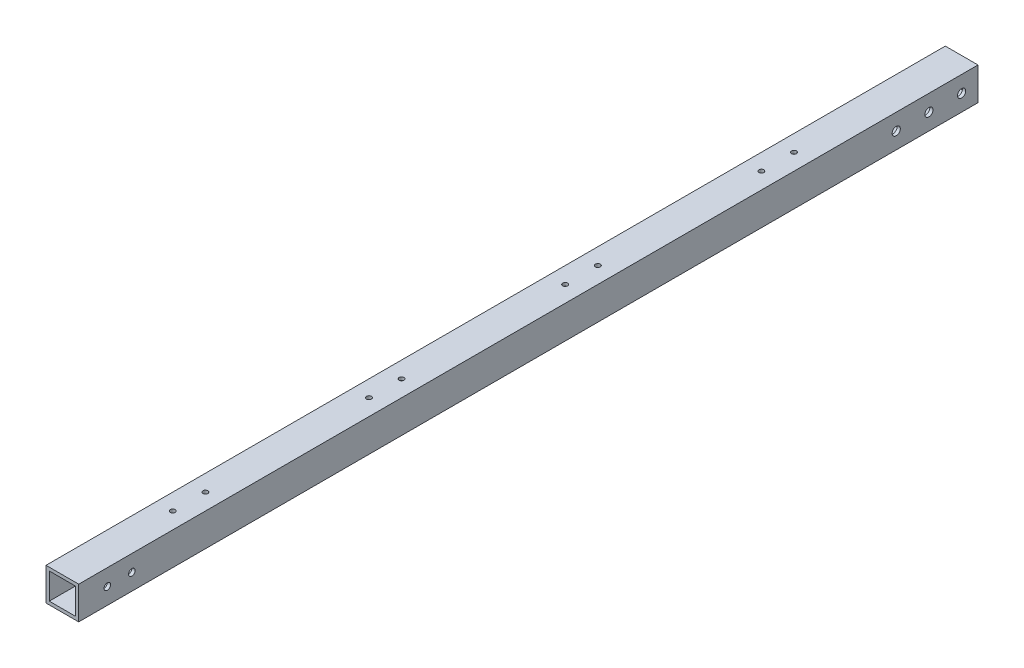
SolidWorks part; units mm, degrees
material "3.0205 (EN-AW 1200)"
ref_plane "前视基准面" through (0, 0, 0) normal (0, 0, 1) x (1, 0, 0)
ref_plane "上视基准面" through (0, 0, 0) normal (0, 1, 0) x (1, 0, 0)
ref_plane "右视基准面" through (0, 0, 0) normal (1, 0, 0) x (0, 0, -1)
sketch "草图1" plane through (0, 0, 0) normal (0, 0, 1) x (1, 0, 0)
  line L1 (-10, -10) -> (10, -10)
  line L2 (-10, -10) -> (-10, 10)
  line L3 (-10, 10) -> (10, 10)
  line L4 (10, -10) -> (10, 10)
  line L5 (-10, -10) -> (10, 10) construction
  line L6 (-10, 10) -> (10, -10) construction
  line L7 (-8, -8) -> (8, -8)
  line L8 (-8, -8) -> (-8, 8)
  line L9 (-8, 8) -> (8, 8)
  line L10 (8, -8) -> (8, 8)
  line L11 (-8, -8) -> (8, 8) construction
  line L12 (-8, 8) -> (8, -8) construction
  point P0 (0, 0)
  point P6 (0, 0)
  dimension "D1" = 16
  dimension "D2" = 20
  dimension "D3" = 20
extrude "凸台-拉伸1" add sketch "草图1" along normal blind 550
sketch "Sketch1" plane through (-10, 0, 0) normal (-1, 0, 0) x (0, 0, 1)
  line L0 (550, 0) -> (541.2704, 0) construction
  line L1 (550, 10) -> (550, -10) construction
  circle A0 centre (532.5, 0) radius 2
  circle A1 centre (517.5, 0) radius 2
  dimension "D1" = 4
  dimension "D2" = 4
  dimension "D4" = 17.5
  dimension "D3" = 15
extrude "Cut-Extrude1" cut sketch "Sketch1" against normal blind 20
sketch "Sketch2" plane through (-10, 0, 0) normal (-1, 0, 0) x (0, 0, 1)
  line L0 (0, 0) -> (73.8513, 0) construction
  line L1 (0, 10) -> (0, -10) construction
  circle A0 centre (10, 0) radius 2.5
  circle A1 centre (30, 0) radius 2.5
  circle A3 centre (50, 0) radius 2.5
  dimension "D3" = 5
  dimension "D4" = 5
  dimension "D5" = 5
  dimension "D1" = 10
  dimension "D2" = 20
  dimension "D6" = 20
extrude "Cut-Extrude2" cut sketch "Sketch2" against normal blind 20
sketch "Sketch5" plane through (0, -10, 0) normal (0, -1, 0) x (1, 0, 0)
  line L0 (0, 0) -> (0, 550) construction
  line L1 (-10, 550) -> (10, 550) construction
  circle A0 centre (0, 482.5) radius 1.5
  circle A1 centre (0, 462.5) radius 1.5
  circle A2 centre (0, 362.5) radius 1.5
  circle A3 centre (0, 342.5) radius 1.5
  circle A4 centre (0, 242.5) radius 1.5
  circle A5 centre (0, 222.5) radius 1.5
  circle A6 centre (0, 122.5) radius 1.5
  circle A7 centre (0, 102.5) radius 1.5
  dimension "D1" = 67.5
  dimension "D3" = 3
  dimension "D4" = 3
  dimension "D5" = 3
  dimension "D6" = 3
  dimension "D7" = 20
  dimension "D8" = 100
  dimension "D9" = 3
  dimension "D10" = 3
  dimension "D12" = 100
  dimension "D13" = 3
  dimension "D14" = 3
  dimension "D15" = 20
  dimension "D16" = 100
  dimension "D2" = 20
  dimension "D11" = 20
extrude "Cut-Extrude3" cut sketch "Sketch5" against normal blind 20
